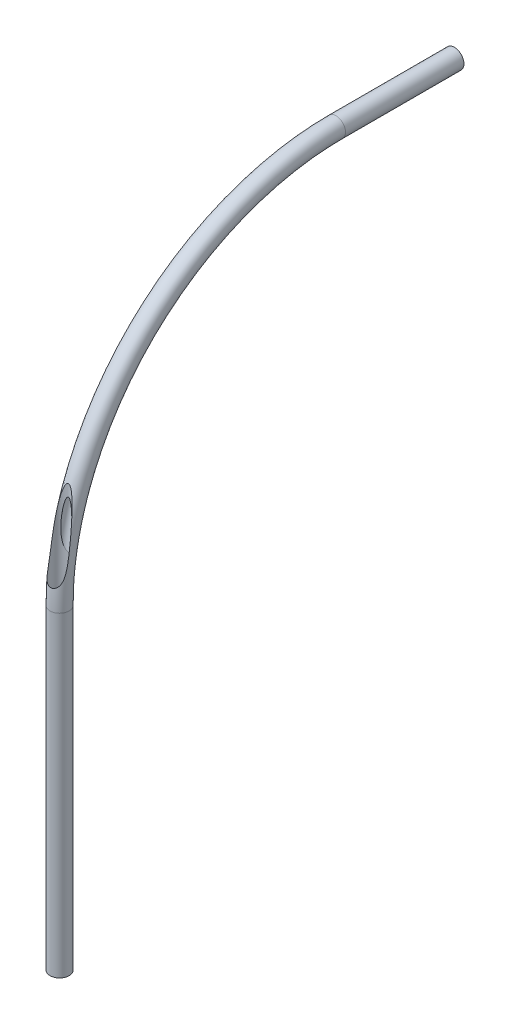
SolidWorks part; units mm, degrees
ref_plane "Ön Düzlem" through (0, 0, 0) normal (0, 0, 1) x (1, 0, 0)
ref_plane "Üst Düzlem" through (0, 0, 0) normal (0, 1, 0) x (1, 0, 0)
ref_plane "Sağ Düzlem" through (0, 0, 0) normal (1, 0, 0) x (0, 0, -1)
sketch "Çizim1" plane through (0, 0, 0) normal (1, 0, 0) x (0, 0, -1)
  line L0 (0, 350) -> (0, 430)
  line L1 (70, 500) -> (100, 500)
  arc A0 (70, 500) -> (0, 430) centre (70, 430) ccw
  point P6 (0, 500)
  dimension "D3" = 70
  dimension "D1" = 150
  dimension "D2" = 100
ref_plane "Düzlem1" through (0, 500, -100) normal (0, 0, -1) x (-1, 0, 0)
sketch "Çizim2" plane through (0, 500, -100) normal (0, 0, -1) x (-1, 0, 0)
  circle A0 centre (0, 0) radius 2.425
  dimension "D1" = 4.85
sweep "Süpür1" add profiles "Çizim2" path "Çizim1"
shell "İç Boşaltma1" thickness 1
sketch "Çizim3" plane through (0, 350, 0) normal (0, -1, 0) x (1, 0, 0)
  circle A0 centre (0, 0) radius 2.25
  dimension "D1" = 4.5
extrude "Kes-Ekstrüzyon1" cut sketch "Çizim3" against normal blind 109
